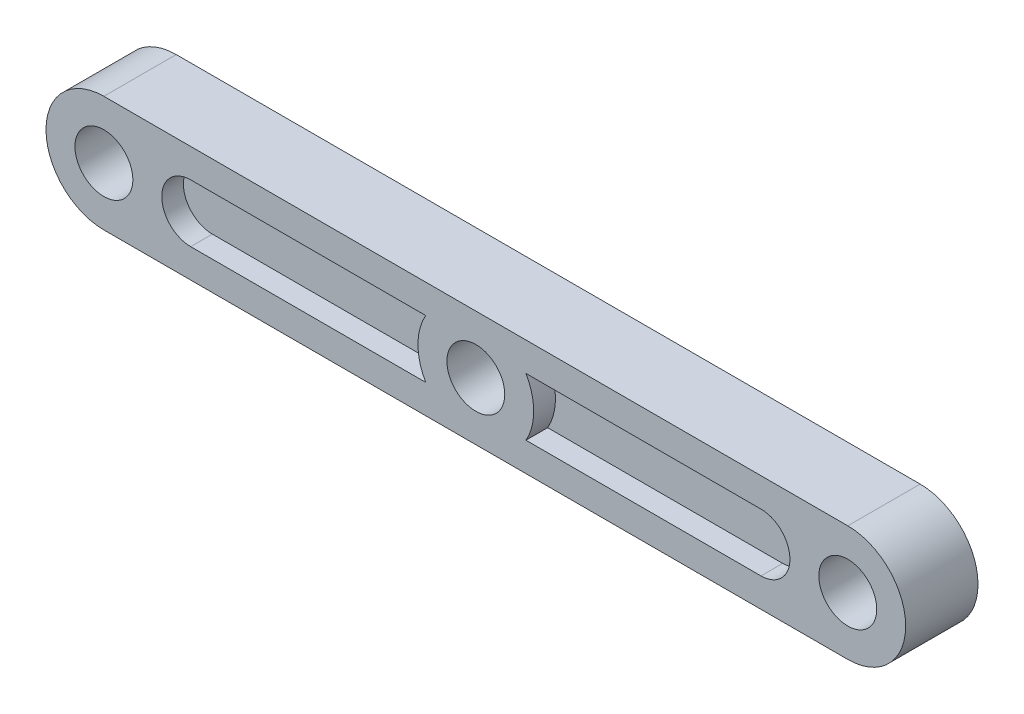
SolidWorks part; units mm, degrees
ref_plane "Front Plane" through (0, 0, 0) normal (0, 0, 1) x (1, 0, 0)
ref_plane "Top Plane" through (0, 0, 0) normal (0, 1, 0) x (1, 0, 0)
ref_plane "Right Plane" through (0, 0, 0) normal (1, 0, 0) x (0, 0, -1)
ref_plane "Plane1" through (0, 0, 0) normal (0, 0, -1) x (-1, 0, 0)
sketch "Sketch1" plane through (0, 0, 0) normal (0, 0, -1) x (-1, 0, 0)
  line L0 (0, 4) -> (-51.4197, 4)
  line L1 (-51.4197, -4) -> (0, -4)
  arc A0 (-51.4197, 4) -> (-51.4197, -4) centre (-51.4197, 0) ccw
  arc A1 (0, -4) -> (0, 4) centre (0, 0) ccw
extrude "Boss-Extrude1" add sketch "Sketch1" against normal blind 5
sketch "Sketch2" plane through (0, 0, 0) normal (0, 0, -1) x (-1, 0, 0)
  line L0 (-6, 2.5) -> (-45.4197, 2.5)
  line L1 (-45.4197, -2.5) -> (-6, -2.5)
  arc A0 (-45.4197, 2.5) -> (-45.4197, -2.5) centre (-45.4197, 0) ccw
  arc A1 (-6, -2.5) -> (-6, 2.5) centre (-6, 0) ccw
extrude "Cut-Extrude1" cut sketch "Sketch2" against normal blind 1.5
sketch "Sketch3" plane through (0, 0, 5) normal (0, 0, 1) x (1, 0, 0)
  line L0 (6, -2) -> (45.4197, -2)
  line L1 (45.4197, 2) -> (6, 2)
  arc A0 (45.4197, -2) -> (45.4197, 2) centre (45.4197, 0) ccw
  arc A1 (6, 2) -> (6, -2) centre (6, 0) ccw
extrude "Cut-Extrude2" cut sketch "Sketch3" against normal blind 1.5
hole_wizard "Ø4.0 (4) Diameter Hole1" positions "Sketch5" profile "Sketch4" hole size "Ø4.0" standard "Ansi Metric"
sketch "Sketch5" plane through (0, 0, 0) normal (0, 0, -1) x (-1, 0, 0)
  point P0 (-51.4197, 0)
  point P1 (0, 0)
sketch "Sketch4" plane through (51.4197, 0, 0) normal (1, 0, 0) x (0, 1, 0)
  line L0 (0, 0) -> (0, 5)
  line L1 (0, 5) -> (2, 5)
  line L2 (2, 5) -> (2, 0)
  line L5 (2, 0) -> (0, 0)
  line L11 (0, -6.35) -> (0, 107.95) construction
  dimension "Thru Hole Dia." = 4
  dimension "Thru Hole Depth" = 5
sketch "Sketch6" plane through (0, 0, 5) normal (0, 0, 1) x (1, 0, 0)
  line L0 (0, 0) -> (51.4197, 0) construction
  circle A0 centre (25.7098, 0) radius 4
extrude "Boss-Extrude2" add sketch "Sketch6" against normal through all
sketch "Sketch7" plane through (0, 0, 5) normal (0, 0, 1) x (1, 0, 0)
  line L0 (0, 0) -> (51.4197, 0) construction
  line L1 (0, 2) -> (51.4197, 2) construction
  circle A1 centre (0, 0) radius 2 construction
  circle A2 centre (51.4197, 0) radius 2 construction
  circle A3 centre (25.7098, 0) radius 2
extrude "Cut-Extrude3" cut sketch "Sketch7" against normal through all
